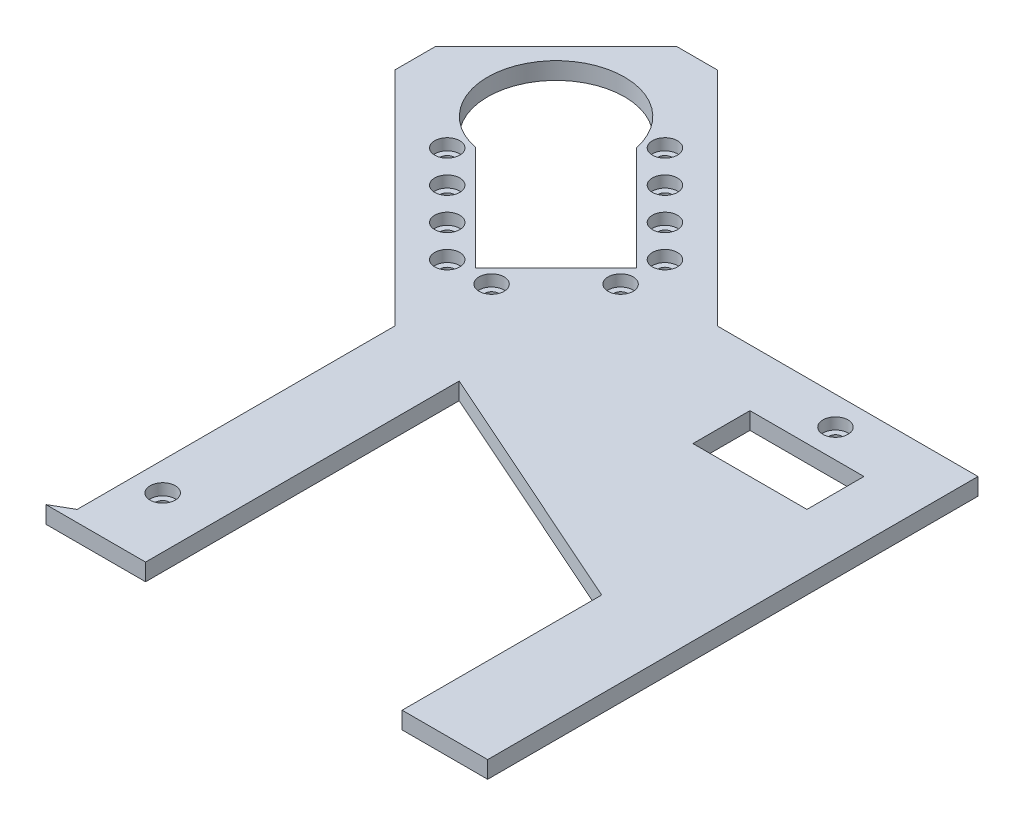
SolidWorks part; units mm, degrees
ref_plane "Front" through (0, 0, 0) normal (0, 0, 1) x (1, 0, 0)
ref_plane "Top" through (0, 0, 0) normal (0, 1, 0) x (1, 0, 0)
ref_plane "Right" through (0, 0, 0) normal (1, 0, 0) x (0, 0, -1)
sketch "草图1" plane through (0, 0, 0) normal (0, 1, 0) x (1, 0, 0)
  line L0 (-45.7157, 114) -> (45.7157, 114)
  line L1 (-74, 0) -> (74, 0) construction
  line L2 (74, -30) -> (91.3205, -20)
  line L3 (91.3205, -20) -> (146.3205, -20)
  line L4 (151.3205, -15) -> (151.3205, 15)
  line L5 (-60, 100) -> (60, -100) construction
  line L6 (-60, -100) -> (60, 100) construction
  line L7 (74, -30) -> (74, -85.7157)
  line L8 (-45.7157, -114) -> (45.7157, -114)
  line L9 (-74, 85.7157) -> (-74, 30)
  line L10 (146.3205, 20) -> (91.3205, 20)
  line L11 (74, 30) -> (91.3205, 20)
  line L12 (0, 100) -> (0, -100) construction
  line L13 (-74, 30) -> (-91.3205, 20)
  line L14 (-146.3205, 20) -> (-91.3205, 20)
  line L15 (-151.3205, -15) -> (-151.3205, 15)
  line L16 (-91.3205, -20) -> (-146.3205, -20)
  line L17 (-74, -30) -> (-91.3205, -20)
  line L18 (-74, -30) -> (-74, -85.7157)
  line L19 (74, 85.7157) -> (74, 30)
  line L20 (91.6777, 152.8909) -> (112.8909, 131.6777)
  line L21 (74, 85.7157) -> (112.8909, 124.6066)
  line L22 (45.7157, 114) -> (84.6066, 152.8909)
  line L23 (-74, 85.7157) -> (-112.8909, 124.6066)
  line L24 (-91.6777, 152.8909) -> (-112.8909, 131.6777)
  line L25 (-45.7157, 114) -> (-84.6066, 152.8909)
  line L26 (74, -85.7157) -> (112.8909, -124.6066)
  line L27 (91.6777, -152.8909) -> (112.8909, -131.6777)
  line L28 (45.7157, -114) -> (84.6066, -152.8909)
  line L29 (-74, -85.7157) -> (-112.8909, -124.6066)
  line L30 (-91.6777, -152.8909) -> (-112.8909, -131.6777)
  line L31 (-45.7157, -114) -> (-84.6066, -152.8909)
  line L32 (-84.6066, 152.8909) -> (-91.6777, 152.8909)
  line L33 (-112.8909, 131.6777) -> (-112.8909, 124.6066)
  line L34 (-151.3205, 15) -> (-146.3205, 20)
  line L35 (-146.3205, -20) -> (-151.3205, -15)
  line L36 (-112.8909, -124.6066) -> (-112.8909, -131.6777)
  line L37 (-84.6066, -152.8909) -> (-91.6777, -152.8909)
  line L38 (84.6066, -152.8909) -> (91.6777, -152.8909)
  line L39 (112.8909, -131.6777) -> (112.8909, -124.6066)
  line L40 (146.3205, -20) -> (151.3205, -15)
  line L41 (151.3205, 15) -> (146.3205, 20)
  line L42 (112.8909, 124.6066) -> (112.8909, 131.6777)
  line L43 (84.6066, 152.8909) -> (91.6777, 152.8909)
  point P0 (0, 0)
  point P12 (74, 30)
  point P16 (74, -30)
extrude "凸台-拉伸1" add sketch "草图1" along normal blind 3
sketch "草图2" plane through (0, 3, 0) normal (0, 1, 0) x (1, 0, 0)
  line L0 (151.3205, 0) -> (87.3942, 0) construction
  line L1 (151.3205, -15) -> (151.3205, 15) construction
  line L2 (103.8205, -10) -> (103.8205, 10)
  line L3 (103.8205, 10) -> (129.6873, 10)
  line L4 (103.8205, -10) -> (129.6873, -10)
  arc A0 (129.6873, -10) -> (129.6873, 10) centre (136.3205, 0) ccw
  point P11 (103.8205, 0)
  dimension "D2" = 24
  dimension "D1" = 15
  dimension "D3" = 20
  dimension "D4" = 32.5
extrude "切除-拉伸1" cut sketch "草图2" against normal up to next
sketch "草图3" plane through (0, 3, 0) normal (0, 1, 0) x (1, 0, 0)
  line L0 (129.6873, 10) -> (103.8205, 10) construction
  line L1 (103.8205, 10) -> (103.8205, -10) construction
  line L2 (151.3205, 0) -> (86.0016, 0) construction
  line L3 (151.3205, -15) -> (151.3205, 15) construction
  point P0 (105.5705, 13.5)
  point P10 (100.3205, 8)
  point P12 (113.5705, 13.5)
  point P13 (121.5705, 13.5)
  point P14 (129.5705, 13.5)
  point P15 (129.5705, -13.5)
  point P16 (121.5705, -13.5)
  point P17 (113.5705, -13.5)
  point P18 (105.5705, -13.5)
  point P19 (100.3205, -8)
  dimension "D1" = 3.5
  dimension "D2" = 1.75
  dimension "D4" = 3.5
  dimension "D5" = 2
  dimension "D3" = 4
hole_wizard "M2 凹头盖螺钉的柱形沉头孔2" positions "3D草图1" profile "草图9" counterbore size "M2" standard "ANSI Metric" end condition through all
sketch3d "3D草图1"
  point P0 (100.3205, 3, -8)
  point P3 (105.5705, 3, -13.5)
  point P6 (113.5705, 3, -13.5)
  point P9 (121.5705, 3, -13.5)
  point P12 (129.5705, 3, -13.5)
  point P15 (100.3205, 3, 8)
  point P18 (105.5705, 3, 13.5)
  point P21 (113.5705, 3, 13.5)
  point P24 (121.5705, 3, 13.5)
  point P27 (129.5705, 3, 13.5)
sketch "草图9" plane through (100.3205, 3, -8) normal (1, 0, 0) x (0, 0, 1)
  line L0 (0, 0) -> (0, 3)
  line L1 (0, 3) -> (1.2, 3)
  line L3 (1.2, 3) -> (1.2, 2)
  line L4 (1.2, 2) -> (2.2, 2)
  line L5 (2.2, 2) -> (2.2, 0)
  line L7 (2.2, 0) -> (0, 0)
  line L11 (0, -6.35) -> (0, 107.95) construction
  dimension "通孔孔直径" = 2.4
  dimension "通孔孔深度" = 3
  dimension "柱形沉头孔直径" = 4.4
  dimension "柱形沉头孔深度" = 2
sketch "草图10" plane through (0, 3, 0) normal (0, 1, 0) x (1, 0, 0)
  line L0 (102.2843, 142.2843) -> (57.3662, 97.3662) construction
  line L1 (112.8909, 131.6777) -> (91.6777, 152.8909) construction
  line L2 (75.7678, 101.6256) -> (61.6256, 115.7678)
  line L3 (61.6256, 115.7678) -> (79.9162, 134.0583)
  line L4 (75.7678, 101.6256) -> (94.0583, 119.9162)
  arc A0 (94.0583, 119.9162) -> (79.9162, 134.0583) centre (91.6777, 131.6777) ccw
  point P9 (68.6967, 108.6967)
  dimension "D1" = 15
  dimension "D2" = 32.5
extrude "切除-拉伸2" cut sketch "草图10" against normal up to next
sketch "草图16" plane through (0, 3, 0) normal (0, 1, 0) x (1, 0, 0)
  line L0 (102.2843, 142.2843) -> (58.019, 98.019) construction
  line L1 (112.8909, 131.6777) -> (91.6777, 152.8909) construction
  line L2 (61.6256, 115.7678) -> (75.7678, 101.6256) construction
  line L3 (79.9162, 134.0583) -> (61.6256, 115.7678) construction
  line L4 (60.3882, 119.4801) -> (80.2149, 139.3067) construction
  point P0 (60.3882, 119.4801)
  point P1 (60.565, 111.8787)
  point P12 (66.045, 125.1369)
  point P13 (71.7019, 130.7938)
  point P14 (77.3588, 136.4506)
  point P15 (96.4506, 117.3588)
  point P16 (90.7938, 111.7019)
  point P17 (85.1369, 106.045)
  point P18 (79.4801, 100.3882)
  point P19 (71.8787, 100.565)
  dimension "D1" = 3.5
  dimension "D2" = 2
  dimension "D3" = 1.75
  dimension "D4" = 3.5
  dimension "D5" = 8
  dimension "D6" = 8
  dimension "D7" = 8
hole_wizard "M2 凹头盖螺钉的柱形沉头孔3" positions "3D草图3" profile "草图17" counterbore size "M2" standard "ANSI Metric" end condition through all
sketch3d "3D草图3"
  point P0 (60.3882, 3, -119.4801)
  point P3 (66.045, 3, -125.1369)
  point P6 (71.7019, 3, -130.7938)
  point P9 (77.3588, 3, -136.4506)
  point P12 (60.565, 3, -111.8787)
  point P15 (71.8787, 3, -100.565)
  point P18 (79.4801, 3, -100.3882)
  point P21 (85.1369, 3, -106.045)
  point P24 (90.7938, 3, -111.7019)
  point P27 (96.4506, 3, -117.3588)
sketch "草图17" plane through (60.3882, 3, -119.4801) normal (1, 0, 0) x (0, 0, 1)
  line L0 (0, 0) -> (0, 3)
  line L1 (0, 3) -> (1.2, 3)
  line L3 (1.2, 3) -> (1.2, 2)
  line L4 (1.2, 2) -> (2.2, 2)
  line L5 (2.2, 2) -> (2.2, 0)
  line L7 (2.2, 0) -> (0, 0)
  line L11 (0, -6.35) -> (0, 107.95) construction
  dimension "通孔孔直径" = 2.4
  dimension "通孔孔深度" = 3
  dimension "柱形沉头孔直径" = 4.4
  dimension "柱形沉头孔深度" = 2
mirror "镜向5" about plane through (0, 0, 0) normal (1, 0, 0) of "切除-拉伸1", "M2 凹头盖螺钉的柱形沉头孔2"
mirror "镜向6" about plane through (0, 0, 0) normal (1, 0, 0) of "切除-拉伸2", "M2 凹头盖螺钉的柱形沉头孔3"
mirror "镜向7" about plane through (0, 0, 0) normal (0, 0, 1) of "切除-拉伸2", "M2 凹头盖螺钉的柱形沉头孔3", "镜向6"
sketch "草图18" plane through (0, 3, 0) normal (0, 1, 0) x (1, 0, 0)
  line L0 (0, 114) -> (0, -114) construction
  line L1 (45.7157, 114) -> (-45.7157, 114) construction
  line L2 (-45.7157, -114) -> (45.7157, -114) construction
  line L3 (-151.3205, 0) -> (151.3205, 0) construction
  line L4 (-151.3205, 15) -> (-151.3205, -15) construction
  line L5 (-60, -28) -> (-15, -28)
  line L6 (-15, -28) -> (-15, -63)
  line L7 (-15, -63) -> (-60, -83)
  line L8 (-60, -83) -> (-60, -28)
  line L12 (10, -94) -> (30, -94)
  line L13 (-10, -94) -> (-30, -94)
  line L14 (-10, -94) -> (-10, -104)
  line L15 (-10, -104) -> (-30, -104)
  line L16 (-30, -94) -> (-30, -104)
  line L17 (-10, -94) -> (-30, -104) construction
  line L18 (-10, -104) -> (-30, -94) construction
  line L19 (10, -104) -> (30, -104)
  line L20 (10, -94) -> (10, -104)
  line L21 (30, -94) -> (30, -104)
  line L22 (15, -63) -> (60, -83)
  line L23 (60, -83) -> (60, -28)
  line L25 (15, -28) -> (15, -63)
  line L26 (60, -28) -> (15, -28)
  line L27 (-10, 104) -> (-30, 104)
  line L28 (-30, 94) -> (-30, 104)
  line L29 (-10, 94) -> (-30, 94)
  line L30 (-10, 94) -> (-10, 104)
  line L31 (30, 94) -> (30, 104)
  line L32 (10, 104) -> (30, 104)
  line L33 (10, 94) -> (10, 104)
  line L34 (10, 94) -> (30, 94)
  line L35 (15, 63) -> (60, 83)
  line L36 (60, 83) -> (60, 28)
  line L37 (60, 28) -> (15, 28)
  line L38 (15, 28) -> (15, 63)
  line L39 (-15, 28) -> (-15, 63)
  line L40 (-60, 28) -> (-15, 28)
  line L41 (-60, 83) -> (-60, 28)
  line L42 (-15, 63) -> (-60, 83)
  point P17 (-20, -99)
  point P32 (0, -20)
  point P33 (0, -10)
  dimension "D5" = 60
  dimension "D6" = 45
  dimension "D7" = 55
  dimension "D8" = 35
  dimension "D9" = 20
  dimension "D10" = 10
  dimension "D11" = 10
  dimension "D12" = 10
extrude "切除-拉伸3" cut sketch "草图18" against normal up to next
sketch "草图19" plane through (0, 3, 0) normal (0, 1, 0) x (1, 0, 0)
  line L0 (0, 114) -> (0, -114) construction
  line L1 (45.7157, 114) -> (-45.7157, 114) construction
  line L2 (-45.7157, -114) -> (45.7157, -114) construction
  line L3 (-151.3205, 0) -> (151.3205, 0) construction
  line L4 (-151.3205, 15) -> (-151.3205, -15) construction
  line L5 (-10, 94) -> (-10, 104) construction
  point P0 (-20, 109)
  point P14 (20, 109)
  point P15 (20, -109)
  point P16 (-20, -109)
  point P17 (-20, 0)
  point P18 (20, 0)
  dimension "D1" = 5
  dimension "D2" = 10
hole_wizard "M2 凹头盖螺钉的柱形沉头孔4" positions "3D草图4" profile "草图20" counterbore size "M2" standard "ANSI Metric" end condition through all
sketch3d "3D草图4"
  point P0 (-20, 3, 109)
  point P3 (20, 3, 109)
  point P6 (-20, 3, -109)
  point P9 (20, 3, -109)
sketch "草图20" plane through (-20, 3, 109) normal (1, 0, 0) x (0, 0, 1)
  line L0 (0, 0) -> (0, 3)
  line L1 (0, 3) -> (1.2, 3)
  line L3 (1.2, 3) -> (1.2, 2)
  line L4 (1.2, 2) -> (2.2, 2)
  line L5 (2.2, 2) -> (2.2, 0)
  line L7 (2.2, 0) -> (0, 0)
  line L11 (0, -6.35) -> (0, 107.95) construction
  dimension "通孔孔直径" = 2.4
  dimension "通孔孔深度" = 3
  dimension "柱形沉头孔直径" = 4.4
  dimension "柱形沉头孔深度" = 2
sketch "草图21" plane through (0, 3, 0) normal (0, 1, 0) x (1, 0, 0)
  line L0 (-74, 85.7157) -> (-74, 30) construction
  line L1 (74, 30) -> (74, 85.7157) construction
  line L2 (-60, 28) -> (-15, 28) construction
  line L3 (15, 28) -> (60, 28) construction
  point P0 (-69, 40)
  point P1 (69, 40)
  point P6 (-69, 0)
  point P11 (69, 0)
  dimension "D1" = 5
  dimension "D2" = 5
  dimension "D3" = 12
  dimension "D4" = 12
  dimension "D5" = 40
hole_wizard "M2 凹头盖螺钉的柱形沉头孔5" positions "3D草图5" profile "草图22" counterbore size "M2" standard "ANSI Metric" end condition through all
sketch3d "3D草图5"
  point P0 (-69, 3, -40)
  point P3 (69, 3, -40)
sketch "草图22" plane through (-69, 3, -40) normal (1, 0, 0) x (0, 0, 1)
  line L0 (0, 0) -> (0, 3)
  line L1 (0, 3) -> (1.2, 3)
  line L3 (1.2, 3) -> (1.2, 2)
  line L4 (1.2, 2) -> (2.2, 2)
  line L5 (2.2, 2) -> (2.2, 0)
  line L7 (2.2, 0) -> (0, 0)
  line L11 (0, -6.35) -> (0, 107.95) construction
  dimension "通孔孔直径" = 2.4
  dimension "通孔孔深度" = 3
  dimension "柱形沉头孔直径" = 4.4
  dimension "柱形沉头孔深度" = 2
mirror "镜向8" about plane through (0, 0, 0) normal (0, 0, 1) of "M2 凹头盖螺钉的柱形沉头孔5"
hole_wizard "M2 凹头盖螺钉的柱形沉头孔6" positions "3D草图6" profile "草图23" counterbore size "M2" standard "ANSI Metric" end condition through all
sketch3d "3D草图6"
  point P0 (-69, 3, 0)
  point P3 (69, 3, 0)
sketch "草图23" plane through (-69, 3, 0) normal (1, 0, 0) x (0, 0, 1)
  line L0 (0, 0) -> (0, 3)
  line L1 (0, 3) -> (1.2, 3)
  line L3 (1.2, 3) -> (1.2, 2)
  line L4 (1.2, 2) -> (2.2, 2)
  line L5 (2.2, 2) -> (2.2, 0)
  line L7 (2.2, 0) -> (0, 0)
  line L11 (0, -6.35) -> (0, 107.95) construction
  dimension "通孔孔直径" = 2.4
  dimension "通孔孔深度" = 3
  dimension "柱形沉头孔直径" = 4.4
  dimension "柱形沉头孔深度" = 2
sketch "草图24" plane through (0, 3, 0) normal (0, 1, 0) x (1, 0, 0)
  line L3 (-10, 28) -> (10, 28)
  line L4 (-10, 28) -> (-10, -28)
  line L5 (-10, -28) -> (10, -28)
  line L6 (10, 28) -> (10, -28)
  line L7 (-10, 28) -> (10, -28) construction
  line L8 (-10, -28) -> (10, 28) construction
  point P0 (0, 0)
  dimension "D1" = 20
  dimension "D2" = 56
extrude "切除-拉伸4" cut sketch "草图24" against normal blind 10
hole_wizard "M2 凹头盖螺钉的柱形沉头孔7" positions "3D草图7" profile "草图25" counterbore size "M2" standard "ANSI Metric" end condition through all
sketch3d "3D草图7"
  point P0 (-20, 3, 0)
  point P3 (20, 3, 0)
sketch "草图25" plane through (-20, 3, 0) normal (1, 0, 0) x (0, 0, 1)
  line L0 (0, 0) -> (0, 3)
  line L1 (0, 3) -> (1.2, 3)
  line L3 (1.2, 3) -> (1.2, 2)
  line L4 (1.2, 2) -> (2.2, 2)
  line L5 (2.2, 2) -> (2.2, 0)
  line L7 (2.2, 0) -> (0, 0)
  line L11 (0, -6.35) -> (0, 107.95) construction
  dimension "通孔孔直径" = 2.4
  dimension "通孔孔深度" = 3
  dimension "柱形沉头孔直径" = 4.4
  dimension "柱形沉头孔深度" = 2
sketch "草图26" plane through (0, 3, 0) normal (0, 1, 0) x (1, 0, 0)
  line L0 (10, 28) -> (-10, 28) construction
  line L1 (-112.8909, 152.8909) -> (0, 152.8909)
  line L2 (-112.8909, 152.8909) -> (-112.8909, 28)
  line L3 (-112.8909, 28) -> (0, 28)
  line L4 (0, 152.8909) -> (0, 28)
extrude "切除-拉伸5" cut sketch "草图26" against normal blind 10 flip side to cut
